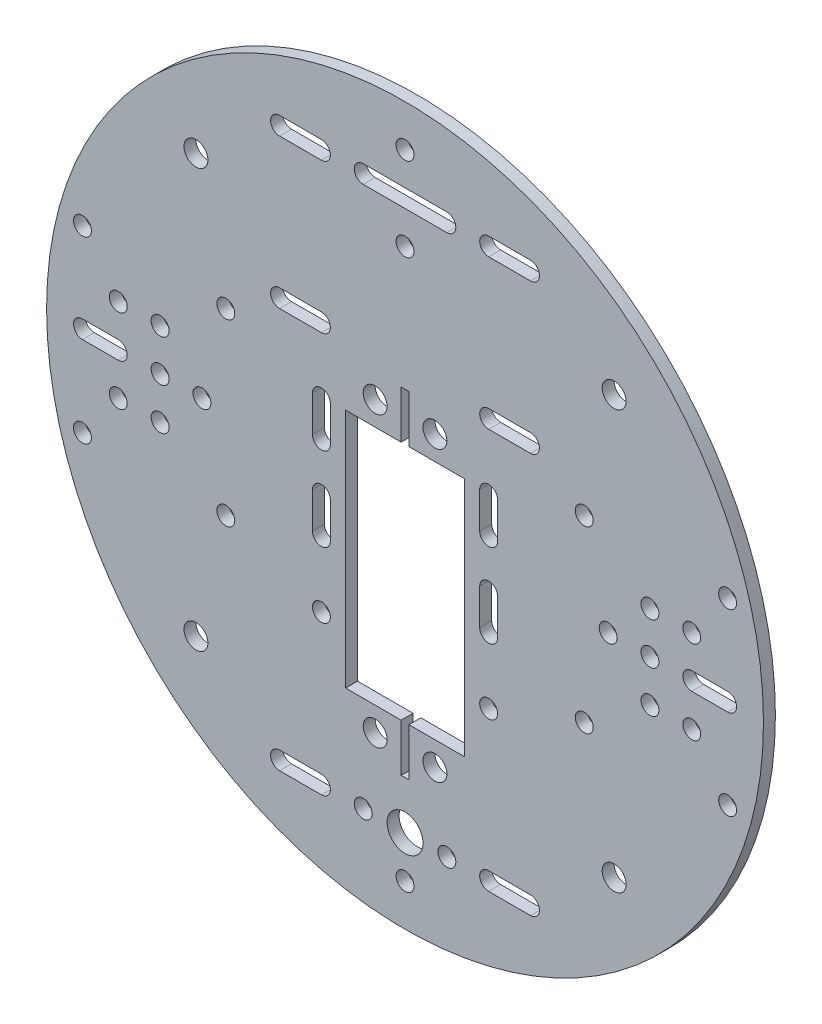
SolidWorks part; units mm, degrees
material "普通碳钢"
ref_plane "前视" through (0, 0, 0) normal (0, 0, 1) x (1, 0, 0)
ref_plane "上视" through (0, 0, 0) normal (0, 1, 0) x (1, 0, 0)
ref_plane "右视" through (0, 0, 0) normal (1, 0, 0) x (0, 0, -1)
sketch "草图2" plane through (0, 0, 0) normal (0, 0, 1) x (1, 0, 0)
  line L0 (1.0372, -12.2442) -> (1.0372, -20.2442)
  line L1 (2.3372, -20.2442) -> (2.3372, -12.2442)
  line L2 (2.3372, -12.2442) -> (11.6467, -12.2442)
  line L3 (11.6467, -12.2442) -> (11.6467, 28.0558)
  line L4 (11.6467, 28.0558) -> (2.3372, 28.0558)
  line L5 (2.3372, 28.0558) -> (2.3372, 36.0558)
  line L6 (1.0372, 36.0558) -> (1.0372, 28.0558)
  line L7 (1.0372, 28.0558) -> (-8.2722, 28.0558)
  line L8 (-8.2722, 28.0558) -> (-8.2722, -12.2442)
  line L9 (-8.2722, -12.2442) -> (1.0372, -12.2442)
  line L10 (14.1872, 13.7581) -> (14.1872, 7.7581)
  line L11 (17.1872, 7.7581) -> (17.1872, 13.7581)
  line L12 (-10.8128, 7.7581) -> (-10.8128, 13.7581)
  line L13 (-13.8128, 13.7581) -> (-13.8128, 7.7581)
  line L14 (-10.8128, 21.7581) -> (-10.8128, 27.7581)
  line L15 (-13.8128, 27.7581) -> (-13.8128, 21.7581)
  line L16 (17.1872, 21.7581) -> (17.1872, 27.7581)
  line L17 (14.1872, 27.7581) -> (14.1872, 21.7581)
  line L18 (15.6872, -29.7419) -> (22.6872, -29.7419)
  line L19 (22.6872, -26.7419) -> (15.6872, -26.7419)
  line L20 (-19.3128, -29.7419) -> (-12.3128, -29.7419)
  line L21 (-12.3128, -26.7419) -> (-19.3128, -26.7419)
  line L22 (-19.3128, 62.2581) -> (-12.3128, 62.2581)
  line L23 (-12.3128, 65.2581) -> (-19.3128, 65.2581)
  line L24 (15.6872, 62.2581) -> (22.6872, 62.2581)
  line L25 (22.6872, 65.2581) -> (15.6872, 65.2581)
  line L26 (-19.3128, 37.2581) -> (-12.3128, 37.2581)
  line L27 (-12.3128, 40.2581) -> (-19.3128, 40.2581)
  line L28 (15.6872, 37.2581) -> (22.6872, 37.2581)
  line L29 (22.6872, 40.2581) -> (15.6872, 40.2581)
  line L30 (49.6872, 16.2581) -> (55.6872, 16.2581)
  line L31 (55.6872, 19.2581) -> (49.6872, 19.2581)
  line L32 (-52.3128, 16.2581) -> (-46.3128, 16.2581)
  line L33 (-46.3128, 19.2581) -> (-52.3128, 19.2581)
  line L34 (-5.3128, 62.2581) -> (8.6872, 62.2581)
  line L35 (8.6872, 65.2581) -> (-5.3128, 65.2581)
  line L36 (1.0372, 36.0558) -> (2.3372, 36.0558)
  line L37 (2.3372, -20.2442) -> (1.0372, -20.2442)
  circle A0 centre (1.6872, 17.7581) radius 60
  circle A1 centre (-3.3128, 32.0508) radius 2
  circle A2 centre (6.6872, -16.2492) radius 2
  circle A3 centre (-3.3128, -16.2492) radius 2
  circle A4 centre (-28.3128, 32.7581) radius 1.5
  circle A5 centre (-52.3128, 32.7581) radius 1.5
  circle A6 centre (-28.3128, 2.7581) radius 1.5
  circle A7 centre (-52.3128, 2.7581) radius 1.5
  circle A8 centre (31.6872, 32.7581) radius 1.5
  circle A9 centre (55.6872, 32.7581) radius 1.5
  circle A10 centre (31.6872, 2.7581) radius 1.5
  circle A11 centre (55.6872, 2.7581) radius 1.5
  circle A12 centre (36.689, -17.2436) radius 2
  circle A13 centre (-33.3145, -17.2436) radius 2
  circle A14 centre (-33.3145, 52.7599) radius 2
  circle A15 centre (36.689, 52.7599) radius 2
  circle A16 centre (-12.3128, -3.2419) radius 1.5
  circle A17 centre (15.6872, -3.2419) radius 1.5
  circle A18 centre (42.6872, 24.7581) radius 1.5
  circle A19 centre (42.6872, 10.7581) radius 1.5
  circle A20 centre (35.6872, 17.7581) radius 1.5
  circle A21 centre (-39.3128, 24.7581) radius 1.5
  circle A22 centre (-39.3128, 10.7581) radius 1.5
  circle A23 centre (-32.3128, 17.7581) radius 1.5
  circle A24 centre (1.6872, -35.2419) radius 1.5
  circle A25 centre (6.6872, 32.0508) radius 2
  circle A26 centre (1.6872, -28.2419) radius 3
  circle A27 centre (8.6872, -28.2419) radius 1.5
  circle A28 centre (-5.3128, -28.2419) radius 1.5
  circle A29 centre (49.6872, 10.7581) radius 1.5
  circle A30 centre (42.6872, 17.7581) radius 1.5
  circle A31 centre (49.6872, 24.7581) radius 1.5
  circle A32 centre (-39.3128, 17.7581) radius 1.5
  circle A33 centre (-46.3128, 10.7581) radius 1.5
  circle A34 centre (-46.3128, 24.7581) radius 1.5
  circle A35 centre (1.6872, 70.7581) radius 1.5
  circle A36 centre (1.6872, 56.7581) radius 1.5
  arc A37 (14.1872, 7.7581) -> (17.1872, 7.7581) centre (15.6872, 7.7581) ccw
  arc A38 (17.1872, 13.7581) -> (14.1872, 13.7581) centre (15.6872, 13.7581) ccw
  arc A39 (-13.8128, 7.7581) -> (-10.8128, 7.7581) centre (-12.3128, 7.7581) ccw
  arc A40 (-10.8128, 13.7581) -> (-13.8128, 13.7581) centre (-12.3128, 13.7581) ccw
  arc A41 (-13.8128, 21.7581) -> (-10.8128, 21.7581) centre (-12.3128, 21.7581) ccw
  arc A42 (-10.8128, 27.7581) -> (-13.8128, 27.7581) centre (-12.3128, 27.7581) ccw
  arc A43 (17.1872, 27.7581) -> (14.1872, 27.7581) centre (15.6872, 27.7581) ccw
  arc A44 (14.1872, 21.7581) -> (17.1872, 21.7581) centre (15.6872, 21.7581) ccw
  arc A45 (22.6872, -29.7419) -> (22.6872, -26.7419) centre (22.6872, -28.2419) ccw
  arc A46 (15.6872, -26.7419) -> (15.6872, -29.7419) centre (15.6872, -28.2419) ccw
  arc A47 (-12.3128, -29.7419) -> (-12.3128, -26.7419) centre (-12.3128, -28.2419) ccw
  arc A48 (-19.3128, -26.7419) -> (-19.3128, -29.7419) centre (-19.3128, -28.2419) ccw
  arc A49 (-12.3128, 62.2581) -> (-12.3128, 65.2581) centre (-12.3128, 63.7581) ccw
  arc A50 (-19.3128, 65.2581) -> (-19.3128, 62.2581) centre (-19.3128, 63.7581) ccw
  arc A51 (22.6872, 62.2581) -> (22.6872, 65.2581) centre (22.6872, 63.7581) ccw
  arc A52 (15.6872, 65.2581) -> (15.6872, 62.2581) centre (15.6872, 63.7581) ccw
  arc A53 (-19.3128, 40.2581) -> (-19.3128, 37.2581) centre (-19.3128, 38.7581) ccw
  arc A54 (-12.3128, 37.2581) -> (-12.3128, 40.2581) centre (-12.3128, 38.7581) ccw
  arc A55 (22.6872, 37.2581) -> (22.6872, 40.2581) centre (22.6872, 38.7581) ccw
  arc A56 (15.6872, 40.2581) -> (15.6872, 37.2581) centre (15.6872, 38.7581) ccw
  arc A57 (55.6872, 16.2581) -> (55.6872, 19.2581) centre (55.6872, 17.7581) ccw
  arc A58 (49.6872, 19.2581) -> (49.6872, 16.2581) centre (49.6872, 17.7581) ccw
  arc A59 (-52.3128, 19.2581) -> (-52.3128, 16.2581) centre (-52.3128, 17.7581) ccw
  arc A60 (-46.3128, 16.2581) -> (-46.3128, 19.2581) centre (-46.3128, 17.7581) ccw
  arc A61 (-5.3128, 65.2581) -> (-5.3128, 62.2581) centre (-5.3128, 63.7581) ccw
  arc A62 (8.6872, 62.2581) -> (8.6872, 65.2581) centre (8.6872, 63.7581) ccw
  dimension "D1" = 3
extrude "凸台-拉伸1" add sketch "草图2" along normal blind 2
